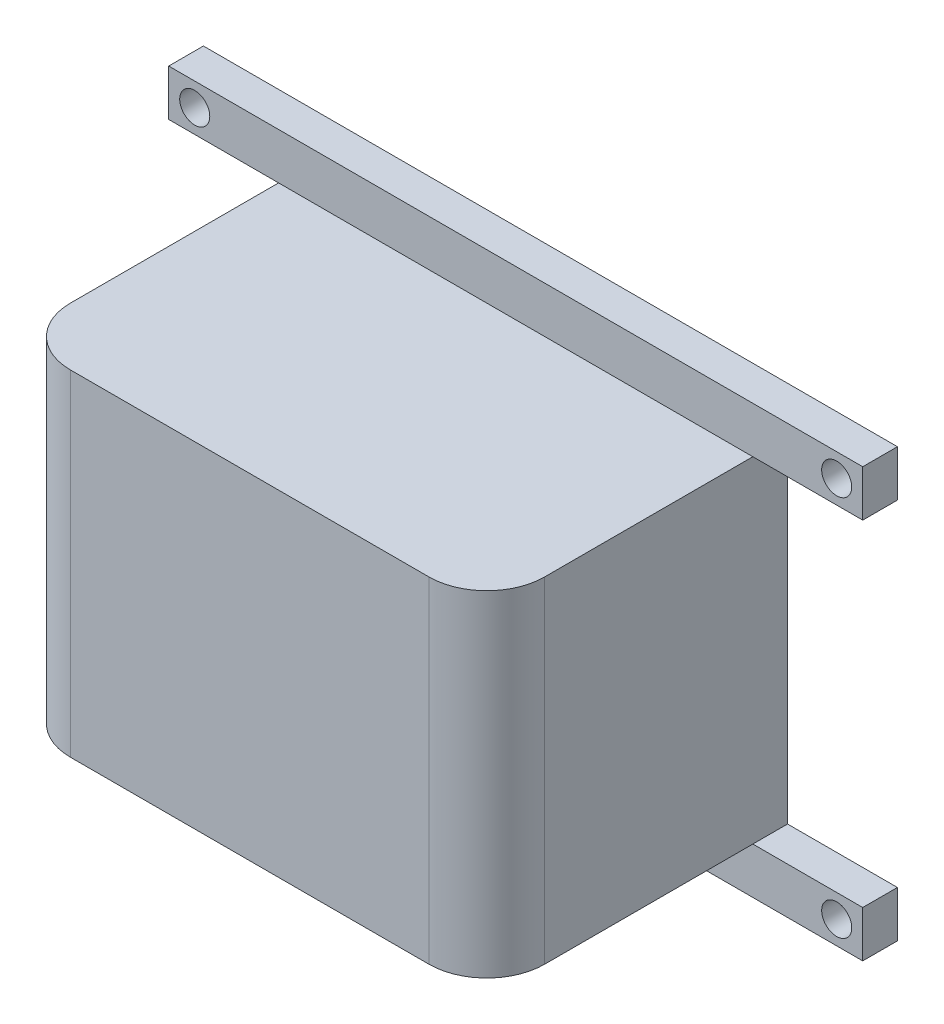
SolidWorks part; units mm, degrees
ref_plane "Plan de face" through (0, 0, 0) normal (0, 0, 1) x (1, 0, 0)
ref_plane "Plan de dessus" through (0, 0, 0) normal (0, 1, 0) x (1, 0, 0)
ref_plane "Plan de droite" through (0, 0, 0) normal (1, 0, 0) x (0, 0, -1)
sketch "Esquisse1" plane through (0, 0, 0) normal (0, 0, 1) x (1, 0, 0)
  line L0 (205, 0) -> (-205, 0) construction
  line L1 (0, -185) -> (0, 185) construction
  line L2 (300, 185) -> (-300, 185)
  line L3 (-300, 185) -> (-300, 145)
  line L4 (-300, 145) -> (-205, 145)
  line L5 (-205, 145) -> (-205, -145)
  line L6 (-300, -145) -> (-205, -145)
  line L7 (-300, -185) -> (-300, -145)
  line L8 (300, -185) -> (-300, -185)
  line L9 (300, -185) -> (300, -145)
  line L10 (300, -145) -> (205, -145)
  line L11 (205, 145) -> (205, -145)
  line L12 (300, 145) -> (205, 145)
  line L13 (300, 185) -> (300, 145)
  point P13 (0, 0)
  dimension "D1" = 600
  dimension "D2" = 410
  dimension "D3" = 370
  dimension "D4" = 40
extrude "Boss.-Extru.1" add sketch "Esquisse1" along normal blind 30
sketch "Esquisse2" plane through (0, 0, 30) normal (0, 0, 1) x (1, 0, 0)
  line L0 (0, 0) -> (-205, 0) construction
  line L1 (-205, 145) -> (-205, -145) construction
  line L2 (0, 0) -> (0, 185) construction
  line L3 (300, 185) -> (-300, 185) construction
  circle A0 centre (-277.5, 165) radius 13
  circle A1 centre (277.5, 165) radius 13
  circle A2 centre (277.5, -165) radius 13
  circle A3 centre (-277.5, -165) radius 13
  dimension "D1" = 555
  dimension "D2" = 330
  dimension "D3" = 26
extrude "Enlèv. mat.-Extru.1" cut sketch "Esquisse2" against normal through all both and the other way through all
sketch "Esquisse3" plane through (0, 0, 30) normal (0, 0, 1) x (1, 0, 0)
  line L0 (205, 0) -> (-205, 0) construction
  line L1 (0, 0) -> (0, 185) construction
  line L2 (300, 185) -> (-300, 185) construction
  line L3 (205, 145) -> (-205, 145)
  line L4 (-205, 145) -> (-205, -145)
  line L6 (205, -145) -> (-205, -145)
  line L7 (205, 145) -> (205, -145)
  line L8 (-205, 145) -> (-205, -145) construction
  line L9 (205, -145) -> (205, 145) construction
  line L10 (300, -145) -> (205, -145) construction
  point P3 (-239.7047, 195)
  point P13 (0, -185)
  point P15 (0, 0)
  point P16 (205, -130.235)
extrude "Boss.-Extru.2" add sketch "Esquisse3" along normal blind 230
fillet "Congé1" radius 50 2 edges at (205, 0, 260) (-205, 0, 260)
